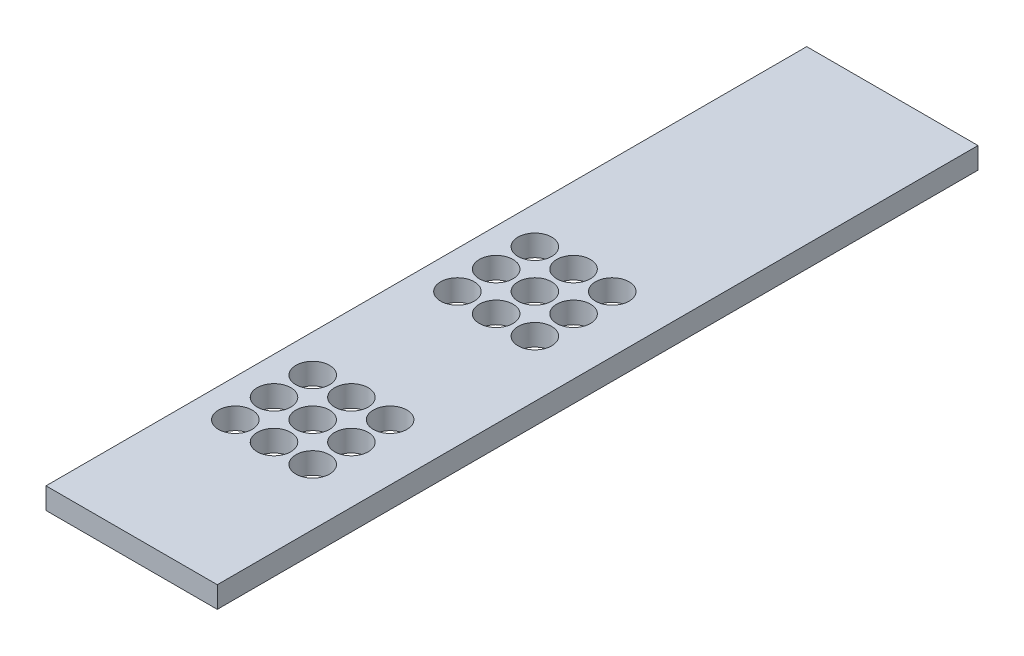
SolidWorks part; units mm, degrees
material "ABS PC"
ref_plane "X-Y Datum" through (0, 0, 0) normal (0, 0, 1) x (1, 0, 0)
ref_plane "X-Z Datum" through (0, 0, 0) normal (0, 1, 0) x (1, 0, 0)
ref_plane "Y-Z Datum" through (0, 0, 0) normal (1, 0, 0) x (0, 0, -1)
sketch "Sketch1" plane through (0, 0, 0) normal (0, 0, 1) x (1, 0, 0)
  line L1 (-25.4444, -3.175) -> (25.4444, -3.175)
  line L2 (-25.4444, -3.175) -> (-25.4444, 3.175)
  line L3 (-25.4444, 3.175) -> (25.4444, 3.175)
  line L4 (25.4444, -3.175) -> (25.4444, 3.175)
  line L5 (-25.4444, -3.175) -> (25.4444, 3.175) construction
  line L6 (-25.4444, 3.175) -> (25.4444, -3.175) construction
  point P0 (0, 0)
  dimension "D1" = 6.35
  dimension "D2" = 50.8889
extrude "Boss-Extrude1" add sketch "Sketch1" along normal blind 225.999
sketch "Sketch3" plane through (0, 3.175, 0) normal (0, 1, 0) x (1, 0, 0)
  line L0 (25.4444, -225.999) -> (25.4444, 0) construction
  circle A0 centre (8.6695, -180.8759) radius 5
  dimension "D2" = 10
  dimension "D1" = 16.775
  dimension "D3" = 21.4808
extrude "Cut-Extrude1" cut sketch "Sketch3" against normal through all
pattern_linear "LPattern1" count 3 spacing 11.5 along (-1, 0, 0) count 3 spacing 11.5 along (0, 0, -1) of "Cut-Extrude1"
pattern_linear "LPattern2" count 2 spacing 66 along (0, 0, -1) of "LPattern1", "Cut-Extrude1"
